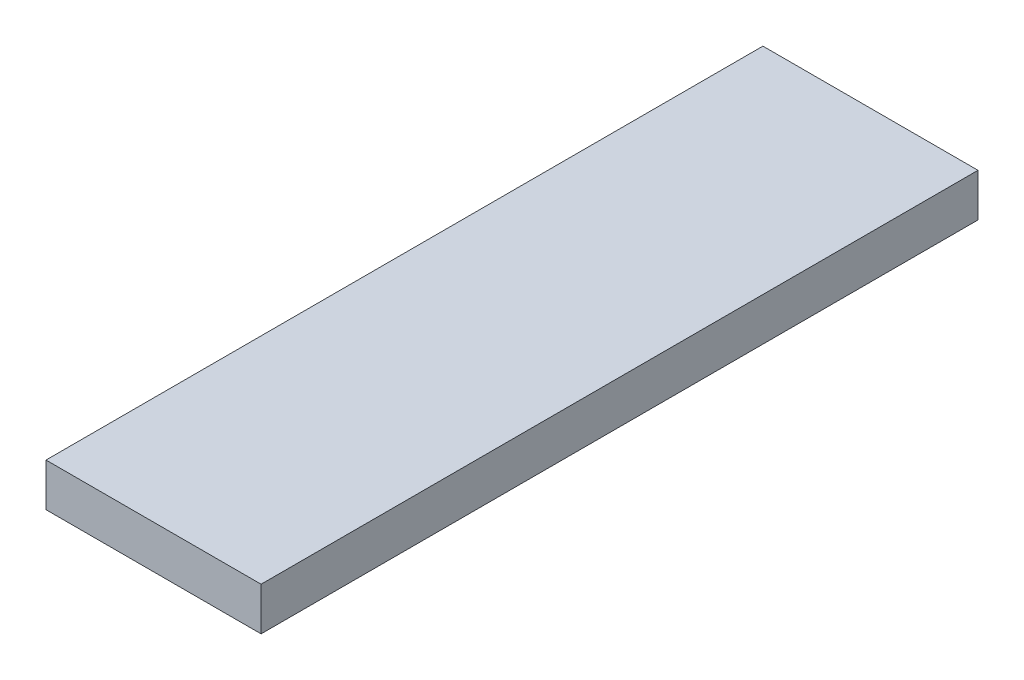
SolidWorks part; units mm, degrees
material "Pine"
ref_plane "Front Plane" through (0, 0, 0) normal (0, 0, 1) x (1, 0, 0)
ref_plane "Top Plane" through (0, 0, 0) normal (0, 1, 0) x (1, 0, 0)
ref_plane "Right Plane" through (0, 0, 0) normal (1, 0, 0) x (0, 0, -1)
sketch "Sketch1" plane through (0, 0, 0) normal (0, 0, 1) x (1, 0, 0)
  line L1 (0, 0) -> (190.5, 0)
  line L2 (0, 0) -> (0, 38.1)
  line L3 (0, 38.1) -> (190.5, 38.1)
  line L4 (190.5, 0) -> (190.5, 38.1)
  dimension "D1" = 190.5
  dimension "D2" = 38.1
extrude "Boss-Extrude1" add sketch "Sketch1" along normal blind 635
sketch "Sketch2" plane through (0, 0, 0) normal (0, 0, -1) x (-1, 0, 0)
  line L1 (-190.5, 0) -> (-190.5, 38.1) construction
  line L2 (0, 38.1) -> (0, 0) construction
  line L3 (-95.25, 19.05) -> (-190.5, 19.05) construction
  line L4 (-95.25, 19.05) -> (0, 19.05) construction
  circle A0 centre (-142.875, 19.05) radius 0.8763
  circle A1 centre (-47.625, 19.05) radius 0.8763
  dimension "D1" = 1.7526
sketch "Sketch3" plane through (0, 0, 0) normal (0, -1, 0) x (1, 0, 0)
  line L0 (95.25, 635) -> (95.25, 590.55) construction
  line L1 (0, 635) -> (190.5, 635) construction
  line L2 (95.25, 590.55) -> (95.25, 546.1) construction
  line L3 (190.5, 317.5) -> (0, 317.5) construction
  line L4 (190.5, 635) -> (190.5, 0) construction
  line L5 (0, 635) -> (0, 0) construction
  line L6 (95.25, 317.5) -> (95.25, 361.95) construction
  line L7 (95.25, 317.5) -> (95.25, 273.05) construction
  circle A0 centre (95.25, 612.775) radius 0.8763
  circle A1 centre (95.25, 568.325) radius 0.8763
  circle A2 centre (95.25, 22.225) radius 0.8763
  circle A3 centre (95.25, 66.675) radius 0.8763
  circle A4 centre (95.25, 295.275) radius 0.8763
  circle A5 centre (95.25, 339.725) radius 0.8763
  dimension "D2" = 1.7526
  dimension "D4" = 1.7526
  dimension "D1" = 88.9
  dimension "D3" = 88.9
equation "\"length\"= 20"
equation "\"length\"= 22"
equation "\"length\"= 36"
equation "\"length\"= 26"
equation "\"length\"= 27"
equation "\"length\"= 28"
equation "\"length\"= 39"
equation "\"length\"= 96"
equation "\"length\"= 30"
equation "\"length\"= 32"
